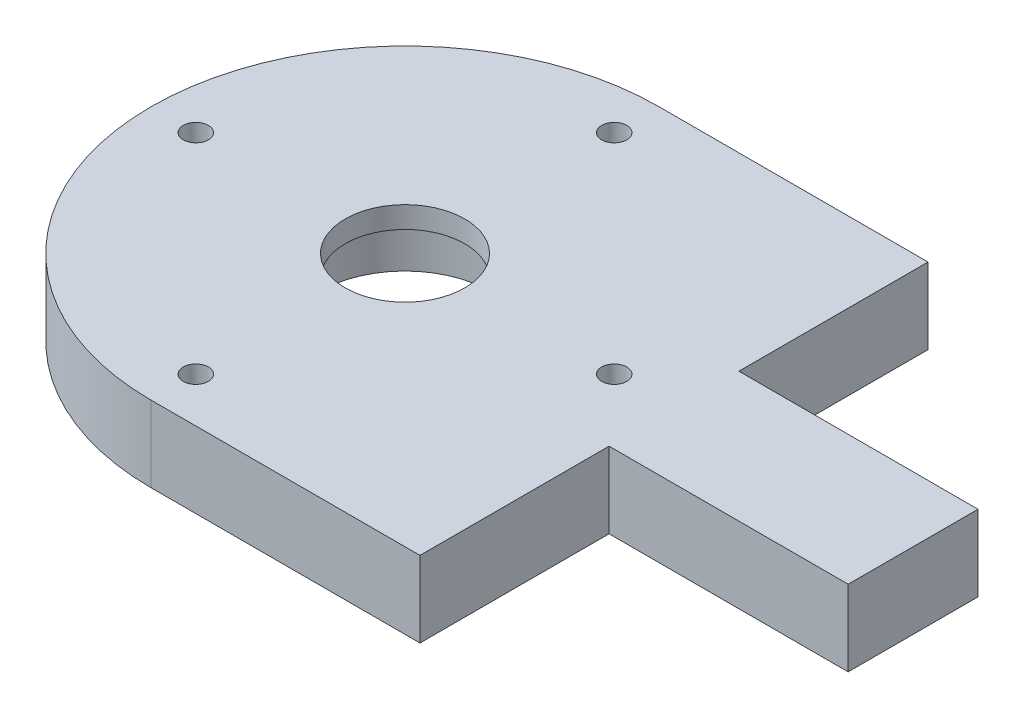
SolidWorks part; units mm, degrees
ref_plane "Front Plane" through (0, 0, 0) normal (0, 0, 1) x (1, 0, 0)
ref_plane "Top Plane" through (0, 0, 0) normal (0, 1, 0) x (1, 0, 0)
ref_plane "Right Plane" through (0, 0, 0) normal (1, 0, 0) x (0, 0, -1)
sketch "Sketch1" plane through (0, 0, 0) normal (0, 1, 0) x (1, 0, 0)
  line L0 (-137.9, 0) -> (0, 0) construction
  line L1 (-137.9, 42.5) -> (0, 42.5)
  line L6 (-137.9, -42.5) -> (0, -42.5)
  line L7 (-137.9, -35) -> (0, -35) construction
  line L13 (-137.9, 35) -> (0, 35) construction
  line L19 (17.6777, -17.6777) -> (-17.6777, 17.6777) construction
  line L21 (-17.6777, -17.6777) -> (17.6777, 17.6777) construction
  circle A1 centre (-137.9, 0) radius 10
  circle A4 centre (-137.9, 0) radius 14.2875 construction
  circle A5 centre (0, 0) radius 10
  circle A8 centre (-137.9, 0) radius 35 construction
  circle A13 centre (-137.9, 0) radius 42.5
  circle A14 centre (0, 0) radius 42.5
  circle A15 centre (0, 0) radius 35 construction
  circle A16 centre (0, 35) radius 2.1
  circle A17 centre (35, 0) radius 2.1
  circle A18 centre (0, -35) radius 2.1
  circle A19 centre (-35, 0) radius 2.1
  circle A28 centre (-137.9, 0) radius 27.94 construction
  circle A29 centre (0, 0) radius 25 construction
  circle A30 centre (-17.6777, 17.6777) radius 2.1
  circle A31 centre (17.6777, -17.6777) radius 2.1
  circle A32 centre (-17.6777, -17.6777) radius 2.1
  circle A33 centre (17.6777, 17.6777) radius 2.1
  circle A34 centre (-172.9, 0) radius 2.1
  circle A35 centre (-137.9, 35) radius 2.1
  circle A36 centre (-102.9, 0) radius 2.1
  circle A37 centre (-137.9, -35) radius 2.1
  point P45 (-92.6314, 0)
  dimension "D2" = 20
  dimension "D4" = 4.2
  dimension "D5" = 45
  dimension "D6" = 28.575
  dimension "D7" = 20
  dimension "D9" = 55.88
  dimension "D10" = 85
  dimension "D8" = 70
  dimension "D11" = 4.2
  dimension "D12" = 70
  dimension "D14" = 50
  dimension "D15" = 4.2
  dimension "D3" = 137.9
extrude "Boss-Extrude1" add sketch "Sketch1" against normal blind 12.7
sketch "Sketch2" plane through (0, 0, 0) normal (0, 1, 0) x (1, 0, 0)
  circle A0 centre (-137.9, 0) radius 14.2875 construction
  circle A1 centre (0, 0) radius 14.35
  dimension "D1" = 28.575
  dimension "D2" = 28.7
extrude "Cut-Extrude1" cut sketch "Sketch2" against normal blind 8.1
sketch "Sketch3" plane through (0, 0, 0) normal (0, 1, 0) x (1, 0, 0)
  circle A0 centre (-137.9, 0) radius 14.35
  dimension "D1" = 28.7
extrude "Cut-Extrude2" cut sketch "Sketch3" along normal blind 9.1 from surface at -12.7 starting at face at (-137.9, -12.7, 37.1)
sketch "Sketch4" plane through (0, 0, 0) normal (0, 1, 0) x (1, 0, 0)
  line L0 (-162.9, 0) -> (-172.9, 0) construction
  line L1 (-162.9, -4.05) -> (-172.9, -4.05)
  line L2 (-162.9, 4.05) -> (-172.9, 4.05)
  line L3 (-137.9, -35) -> (-127.9, -35) construction
  line L4 (-137.9, -30.95) -> (-127.9, -30.95)
  line L5 (-137.9, -39.05) -> (-127.9, -39.05)
  line L6 (-92.9, 0) -> (-102.9, 0) construction
  line L7 (-92.9, -4.05) -> (-102.9, -4.05)
  line L8 (-92.9, 4.05) -> (-102.9, 4.05)
  line L9 (-137.9, 35) -> (-127.9, 35) construction
  line L10 (-137.9, 39.05) -> (-127.9, 39.05)
  line L11 (-137.9, 30.95) -> (-127.9, 30.95)
  arc A0 (-162.9, -4.05) -> (-162.9, 4.05) centre (-162.9, 0) ccw
  arc A1 (-172.9, 4.05) -> (-172.9, -4.05) centre (-172.9, 0) ccw
  arc A2 (-137.9, -30.95) -> (-137.9, -39.05) centre (-137.9, -35) ccw
  arc A3 (-127.9, -39.05) -> (-127.9, -30.95) centre (-127.9, -35) ccw
  arc A4 (-92.9, -4.05) -> (-92.9, 4.05) centre (-92.9, 0) ccw
  arc A5 (-102.9, 4.05) -> (-102.9, -4.05) centre (-102.9, 0) ccw
  arc A6 (-137.9, 39.05) -> (-137.9, 30.95) centre (-137.9, 35) ccw
  arc A7 (-127.9, 30.95) -> (-127.9, 39.05) centre (-127.9, 35) ccw
  circle A8 centre (-137.9, 0) radius 35 construction
  point P3 (-167.9, 0)
  point P8 (-132.9, -35)
  point P15 (-97.9, 0)
  point P22 (-132.9, 35)
  dimension "D3" = 70
  dimension "D1" = 10
  dimension "D2" = 8.1
extrude "Cut-Extrude3" cut sketch "Sketch4" along normal blind 5 from surface at -12.7 starting at face at (-137.9, -12.7, 14.35)
sketch "Sketch6" plane through (0, 0, 0) normal (0, 1, 0) x (1, 0, 0)
  line L0 (-137.9, 0) -> (-52.9, 0) construction
  line L1 (-92.9, 10.8606) -> (-52.9, 10.8606)
  line L2 (47.9853, 58.1666) -> (-92.9, 58.1666)
  line L3 (47.9853, 58.1666) -> (47.9853, -58.1666)
  line L4 (47.9853, -58.1666) -> (-92.9, -58.1666)
  line L5 (-92.9, 58.1666) -> (-92.9, 10.8606)
  line L6 (-52.9, 10.8606) -> (-52.9, -10.8606)
  line L7 (-52.9, -10.8606) -> (-92.9, -10.8606)
  line L8 (-92.9, -10.8606) -> (-92.9, -58.1666)
  dimension "D1" = 85
  dimension "D2" = 40
extrude "Cut-Extrude4" cut sketch "Sketch6" against normal blind 20
